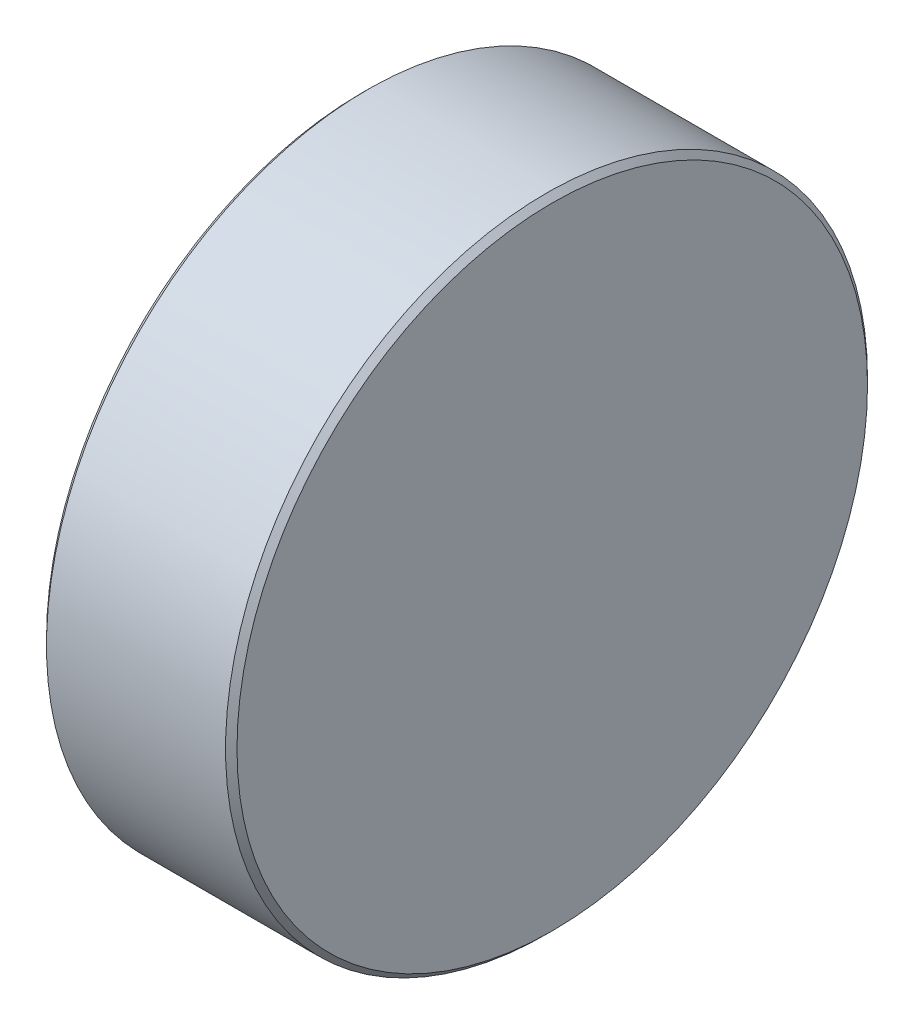
SolidWorks part; units mm, degrees
material "6061 合金"
ref_plane "前视基准面" through (0, 0, 0) normal (0, 0, 1) x (1, 0, 0)
ref_plane "上视基准面" through (0, 0, 0) normal (0, 1, 0) x (1, 0, 0)
ref_plane "右视基准面" through (0, 0, 0) normal (1, 0, 0) x (0, 0, -1)
sketch "草图1" plane through (0, 0, 0) normal (1, 0, 0) x (0, 0, -1)
  circle A0 centre (0, 0) radius 16.85
  dimension "D1" = 33.7
extrude "凸台-拉伸1" add sketch "草图1" along normal blind 10
sketch "草图2" plane through (0, 0, 0) normal (-1, 0, 0) x (0, 0, 1)
  circle A0 centre (0, 0) radius 5.7
  dimension "D1" = 11.4
extrude "凸台-拉伸2" [suppressed] add sketch "草图2" along normal blind 70
chamfer "圆盘外缘倒角_C0.3" distance 0.3 angle 45 2 edges at (0, 0, -16.85) (10, 0, -16.85)
